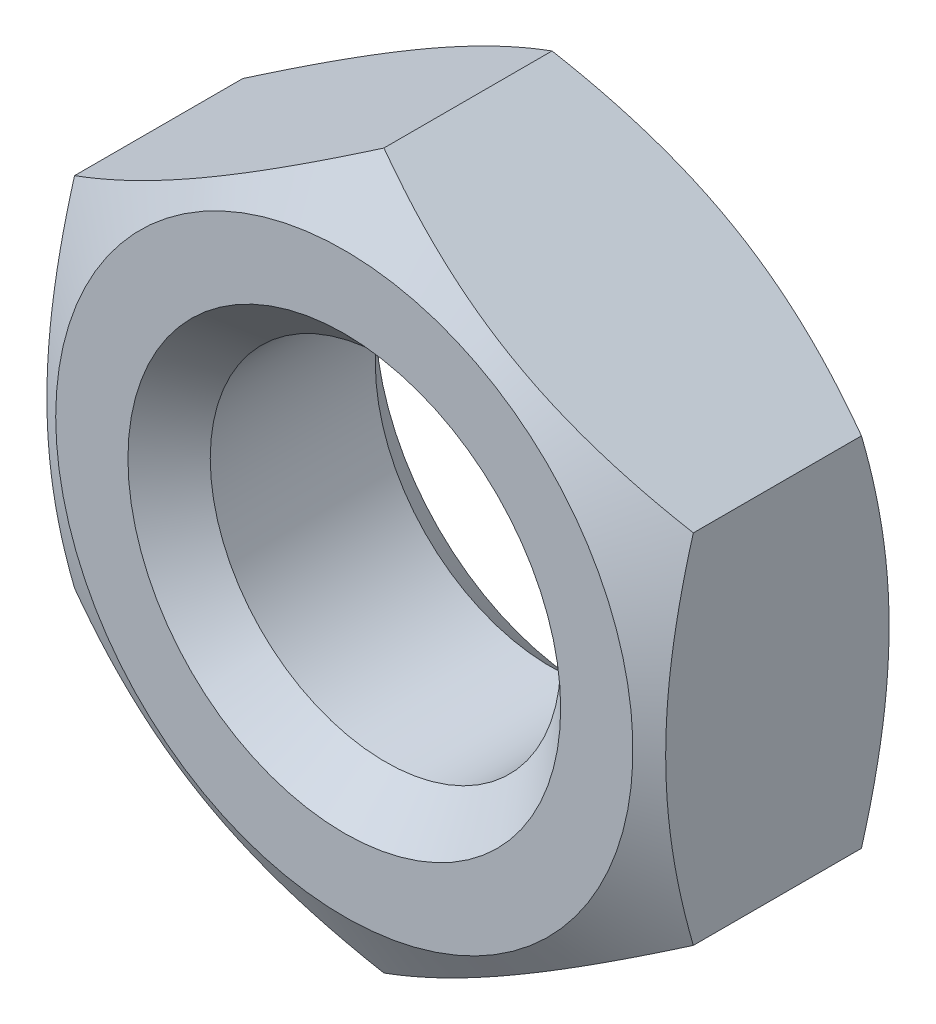
SolidWorks part; units mm, degrees
ref_plane "front" through (0, 0, 0) normal (0, 0, 1) x (1, 0, 0)
ref_plane "top" through (0, 0, 0) normal (0, 1, 0) x (1, 0, 0)
ref_plane "right" through (0, 0, 0) normal (1, 0, 0) x (0, 0, -1)
sketch "Sketch1" plane through (0, 0, 0) normal (1, 0, 0) x (0, 0, -1)
  line L0 (-1.5843, 6.7469) -> (-7.9407, 6.7469)
  line L1 (-7.9407, 6.7469) -> (-9.525, 8.3312)
  line L2 (-9.525, 8.3312) -> (-9.525, 11.1125)
  line L3 (-9.525, 11.1125) -> (-6.7754, 15.875)
  line L4 (-6.7754, 15.875) -> (-2.7496, 15.875)
  line L5 (-2.7496, 15.875) -> (0, 11.1125)
  line L6 (0, 11.1125) -> (0, 8.3312)
  line L7 (0, 8.3312) -> (-1.5843, 6.7469)
  line L8 (-4.7625, 15.875) -> (-4.7625, 26.7712) construction
  line L9 (0, 0) -> (22.4968, 0) construction
  dimension "D1" = 45
  dimension "D2" = 30
  dimension "D3" = 22.225
  dimension "D4" = 13.4937
  dimension "D5" = 16.6624
  dimension "D6" = 31.75
  dimension "D7" = 9.525
ref_axis "Axis1" through (0, 0, -10.3808) along (0, 0, 1)
revolve "Revolve1" add sketch "Sketch1" angle 360 about axis through (0, 0, -10.3808) along (0, 0, 1)
sketch "Sketch2" plane through (0, 0, 0) normal (0, 0, 1) x (1, 0, 0)
  line L1 (0, 13.7555) -> (-11.9126, 6.8777)
  line L2 (-11.9126, 6.8777) -> (-11.9126, -6.8777)
  line L3 (-11.9126, -6.8777) -> (0, -13.7555)
  line L4 (0, -13.7555) -> (11.9126, -6.8777)
  line L5 (11.9126, -6.8777) -> (11.9126, 6.8777)
  line L6 (11.9126, 6.8777) -> (0, 13.7555)
  circle A0 centre (0, 0) radius 11.9126 construction
  dimension "D1" = 23.8252
extrude "Cut-Extrude2" cut sketch "Sketch2" along normal blind 25.4 flip side to cut
